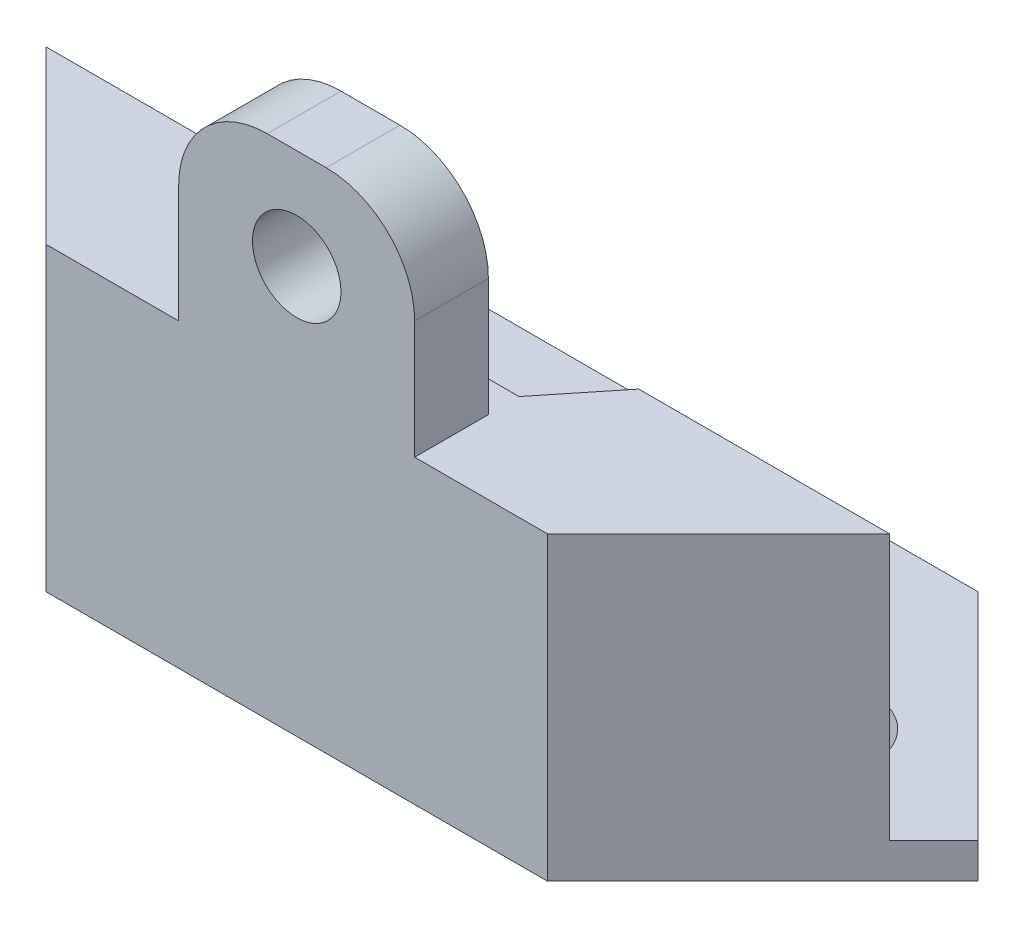
SolidWorks part; units mm, degrees
ref_plane "Plano frontal" through (0, 0, 0) normal (0, 0, 1) x (1, 0, 0)
ref_plane "Plano superior" through (0, 0, 0) normal (0, 1, 0) x (1, 0, 0)
ref_plane "Plano direito" through (0, 0, 0) normal (1, 0, 0) x (0, 0, -1)
sketch "Esboço1" plane through (0, 0, 0) normal (0, 1, 0) x (1, 0, 0)
  line L0 (-24.8219, 0) -> (24.5765, 0) construction
  line L1 (-8.5, 7.3) -> (8.5, 7.3)
  line L2 (-8.5, 7.3) -> (-8.5, -7.3)
  line L3 (-8.5, -7.3) -> (8.5, -7.3)
  line L4 (8.5, 7.3) -> (8.5, -7.3)
  line L5 (-8.5, 7.3) -> (8.5, -7.3) construction
  line L6 (-8.5, -7.3) -> (8.5, 7.3) construction
  line L7 (-8.5, -7.3) -> (-15.8, 0)
  line L8 (-15.8, 0) -> (-8.5, 7.3)
  line L9 (8.5, -7.3) -> (15.8, 0)
  line L10 (15.8, 0) -> (8.5, 7.3)
  point P0 (0, 0)
  dimension "D1" = 17
  dimension "D2" = 14.6
extrude "Ressalto-extrusão1" add sketch "Esboço1" along normal blind 1.2 contours L4 L1 L2 L3 | L8 L7 L2 | L9 L10 L4
sketch "Esboço2" plane through (0, 1.2, 0) normal (0, 1, 0) x (1, 0, 0)
  line L0 (-8.5, -7.3) -> (8.5, -7.3) construction
  line L3 (8.5, -7.3) -> (15.8, 0) construction
  line L4 (14.3, -1.5) -> (8.5, -7.3)
  line L5 (8.5, -7.3) -> (-8.5, -7.3)
  circle A0 centre (-9.75, 0.5) radius 2
  circle A1 centre (0, 3.5) radius 2.0549
  circle A2 centre (9.75, 0.5) radius 2
  point P6 (10.9195, -3.3252)
  dimension "D3" = 4
  dimension "D6" = 4
  dimension "D1" = 19.5
  dimension "D2" = 9.75
  dimension "D4" = 4
  dimension "D5" = 7.8
  dimension "D7" = 10.8
extrude "Corte-extrusão3" cut sketch "Esboço2" against normal through all contours A0 | A1 | A2
sketch "Esboço6" plane through (0, 1.2, 0) normal (0, 1, 0) x (1, 0, 0)
  line L0 (-14.3, -1.5) -> (14.3, -1.5)
  line L1 (-8.5, -7.3) -> (-15.8, 0) construction
  line L2 (8.5, -7.3) -> (15.8, 0) construction
  line L3 (14.3, -1.5) -> (8.5, -7.3)
  line L4 (8.5, -7.3) -> (-8.5, -7.3)
  line L5 (-8.5, -7.3) -> (-14.3, -1.5)
extrude "Ressalto-extrusão4" add sketch "Esboço6" along normal blind 9
sketch "Esboço8" plane through (0, 0, 1.5) normal (0, 0, -1) x (-1, 0, 0)
  line L0 (-14.3, 10.2) -> (-14.3, 1.2) construction
  line L1 (14.3, 10.2) -> (14.3, 1.2) construction
  line L2 (-14.3, 10.2) -> (14.3, 10.2) construction
  circle A0 centre (-9.8, 6.7) radius 1.15
  circle A1 centre (9.75, 6.7) radius 1.15
  dimension "D2" = 2.3
  dimension "D3" = 2.3
  dimension "D1" = 4.5
  dimension "D4" = 4.55
  dimension "D5" = 3.5
  dimension "D6" = 3.5
extrude "Corte-extrusão4" cut sketch "Esboço8" against normal blind 3
sketch "Esboço10" plane through (0, 10.2, 0) normal (0, 1, 0) x (1, 0, 0)
  line L0 (-8.5, -7.3) -> (8.5, -7.3) construction
  line L1 (-4, -4.8) -> (4, -4.8)
  line L2 (-4, -4.8) -> (-4, -7.3)
  line L4 (4, -4.8) -> (4, -7.3)
  line L5 (-4, -4.8) -> (0, -7.3) construction
  line L6 (0, -7.3) -> (4, -4.8) construction
  line L7 (-4, -7.3) -> (4, -7.3)
  point P0 (0, -7.3)
  dimension "D1" = 8
extrude "Ressalto-extrusão5" add sketch "Esboço10" along normal blind 7
sketch "Esboço11" plane through (0, 0, 4.8) normal (0, 0, -1) x (-1, 0, 0)
  line L0 (-4, 10.2) -> (4, 10.2) construction
  circle A0 centre (0, 13.8) radius 1.5
  dimension "D2" = 3
  dimension "D1" = 3.6
extrude "Corte-extrusão5" cut sketch "Esboço11" against normal blind 10
sketch "Esboço12" plane through (0, 10.2, 0) normal (0, 1, 0) x (1, 0, 0)
  line L0 (-3.9578, -3.75) -> (-5.8, -1.5)
  line L1 (14.3, -1.5) -> (-14.3, -1.5) construction
  line L2 (-3.9578, -3.75) -> (3.989, -3.75)
  line L3 (3.989, -3.75) -> (5.8, -1.5)
  line L4 (9.75, -1.5) -> (-9.75, -1.5) construction
  line L5 (-5.8, -1.5) -> (5.8, -1.5)
  dimension "D1" = 8.5
  dimension "D2" = 8.5
  dimension "D3" = 2.25
extrude "Corte-extrusão8" cut sketch "Esboço12" against normal blind 9
fillet "Filete1" radius 3 1 edges at (4, 17.2, 6.05)
fillet "Filete2" radius 3 1 edges at (-4, 17.2, 6.05)
